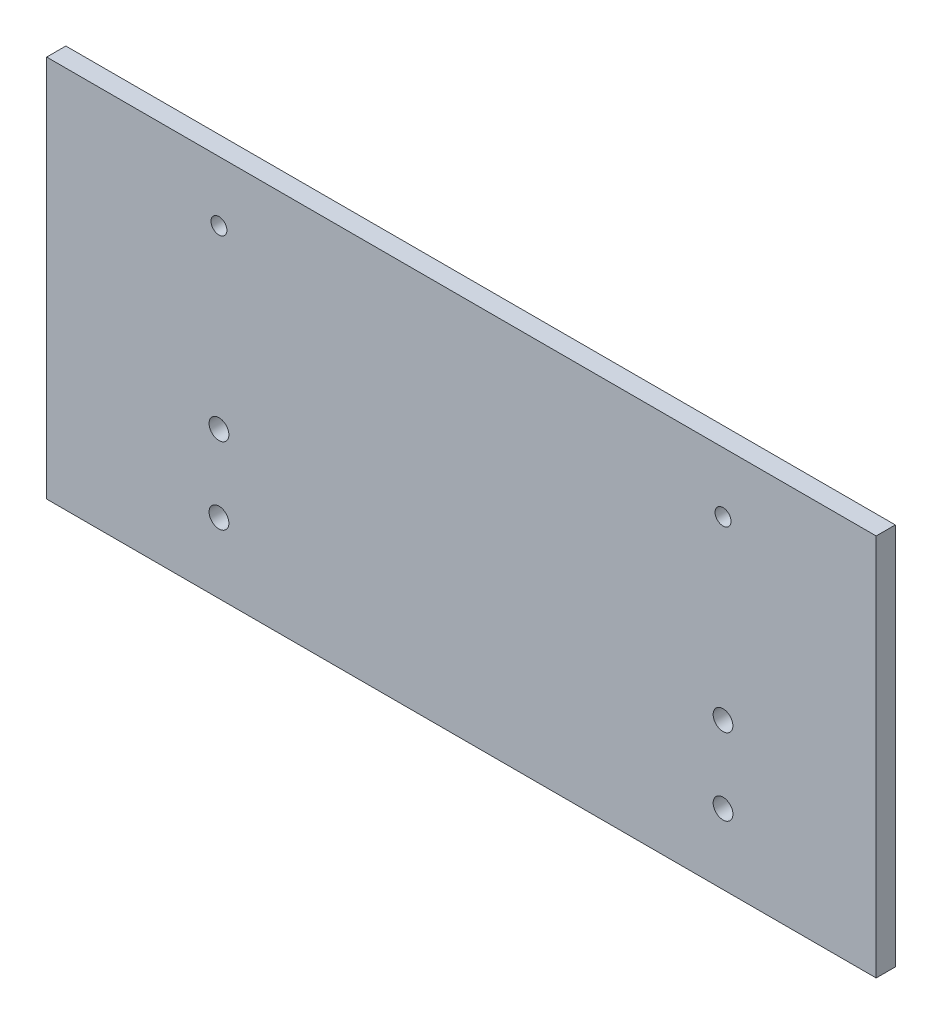
SolidWorks part; units mm, degrees
ref_plane "Front Plane" through (0, 0, 0) normal (0, 0, 1) x (1, 0, 0)
ref_plane "Top Plane" through (0, 0, 0) normal (0, 1, 0) x (1, 0, 0)
ref_plane "Right Plane" through (0, 0, 0) normal (1, 0, 0) x (0, 0, -1)
sketch "Sketch1" plane through (0, 0, 0) normal (0, 0, 1) x (1, 0, 0)
  line L1 (-61.0944, 51.088) -> (68.9056, 51.088)
  line L2 (-61.0944, 51.088) -> (-61.0944, -8.912)
  line L3 (-61.0944, -8.912) -> (68.9056, -8.912)
  line L4 (68.9056, 51.088) -> (68.9056, -8.912)
  circle A0 centre (-34.0944, 14.088) radius 1.55
  circle A1 centre (-34.0944, 2.088) radius 1.55
  circle A2 centre (44.9056, 2.088) radius 1.55
  circle A3 centre (44.9056, 14.088) radius 1.55
  circle A4 centre (-34.0944, 41.688) radius 1.25
  circle A5 centre (44.9056, 41.688) radius 1.25
  point P14 (0, 0)
  point P15 (0, 0)
  point P16 (0, 0)
  point P17 (0, 0)
  dimension "D3" = 3.1
  dimension "D4" = 3.1
  dimension "D5" = 3.1
  dimension "D6" = 3.1
  dimension "D11" = 2.5
  dimension "D12" = 2.5
  dimension "D1" = 130
  dimension "D2" = 60
  dimension "D7" = 79
  dimension "D8" = 12
  dimension "D9" = 27
  dimension "D10" = 11
  dimension "D13" = 27.6
extrude "Boss-Extrude1" add sketch "Sketch1" along normal blind 3
